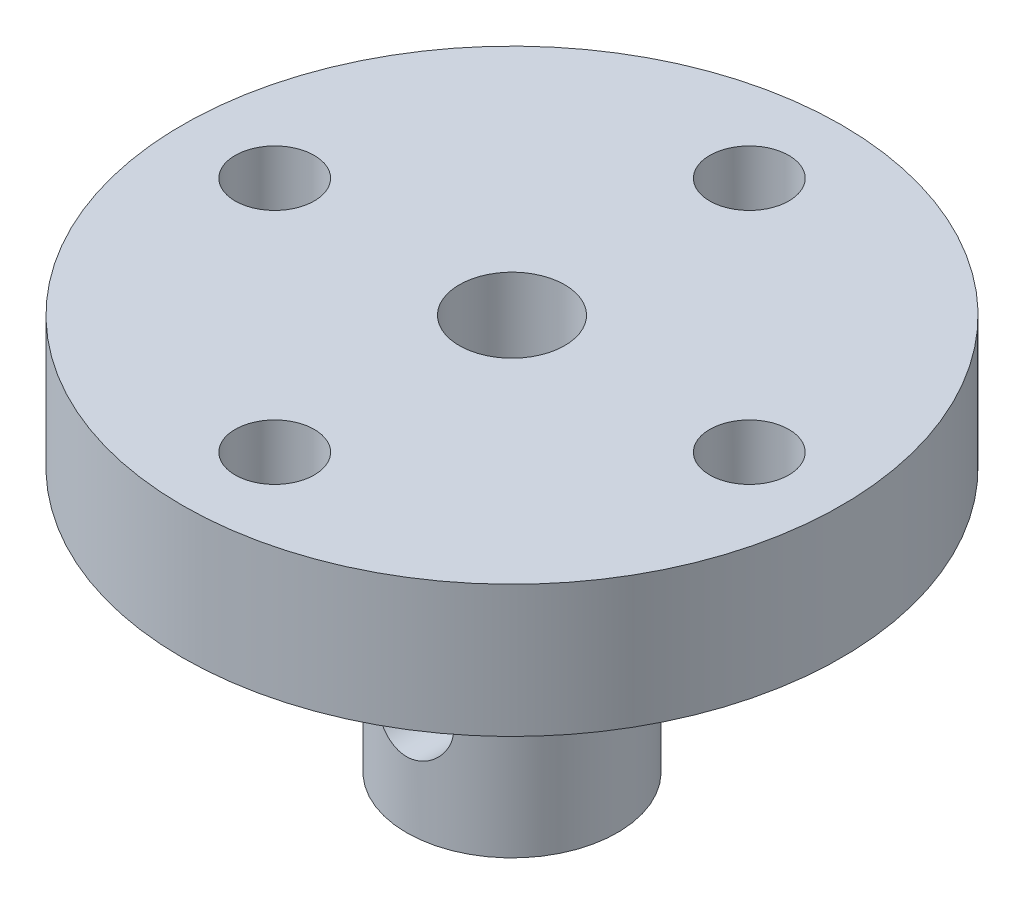
SolidWorks part; units mm, degrees
material "Alloy Steel (SS)"
ref_plane "Front Plane" through (0, 0, 0) normal (0, 0, 1) x (1, 0, 0)
ref_plane "Top Plane" through (0, 0, 0) normal (0, 1, 0) x (1, 0, 0)
ref_plane "Right Plane" through (0, 0, 0) normal (1, 0, 0) x (0, 0, -1)
sketch "Sketch1" plane through (0, 0, 0) normal (0, 1, 0) x (1, 0, 0)
  circle A0 centre (0, 0) radius 4
  dimension "D1" = 8
extrude "Boss-Extrude1" add sketch "Sketch1" along normal blind 10
sketch "Sketch3" plane through (0, 10, 0) normal (0, 1, 0) x (1, 0, 0)
  circle A0 centre (0, 0) radius 12.5
  dimension "D1" = 25
extrude "Boss-Extrude2" add sketch "Sketch3" along normal blind 5
hole_wizard "Ø3.0 (3) Diameter Hole2" positions "3DSketch2" profile "Sketch5" hole size "Ø3.0" standard "ANSI Metric" end condition through all
sketch3d "3DSketch2"
  line L2 (0, 0, 0) -> (0, 0, -4) construction
  line L5 (0, 0, -4) -> (0, 4, -4) construction
  circle A2 centre (0, 0, 0) radius 4 construction
  point P0 (0, 4, -4)
  point P33 (0, 4, 0)
  dimension "D1" = 4
sketch "Sketch5" plane through (0, 4, -4) normal (1, 0, 0) x (0, 1, 0)
  line L0 (0, 0) -> (0, 16.5)
  line L1 (0, 16.5) -> (1.5, 16.5)
  line L2 (1.5, 16.5) -> (1.5, 0)
  line L5 (1.5, 0) -> (0, 0)
  line L11 (0, -6.35) -> (0, 107.95) construction
  dimension "Thru Hole Dia." = 3
  dimension "Thru Hole Depth" = 16.5
sketch "Sketch6" plane through (0, 15, 0) normal (0, 1, 0) x (1, 0, 0)
  circle A0 centre (0, 0) radius 9
  circle A1 centre (-9, 0) radius 1.5
  dimension "D1" = 18
  dimension "D2" = 3
extrude "Cut-Extrude2" cut sketch "Sketch6" against normal blind 10 contours A0 A1 | A0 A1
sketch "Sketch2" plane through (0, 0, 0) normal (0, -1, 0) x (1, 0, 0)
  circle A0 centre (0, 0) radius 2
  dimension "D1" = 4
extrude "Cut-Extrude1" cut sketch "Sketch2" against normal through all
pattern_circular "CirPattern1" count 4 over 360 about axis through (0, 0, 0) along (0, 1, 0) of "Cut-Extrude2"
